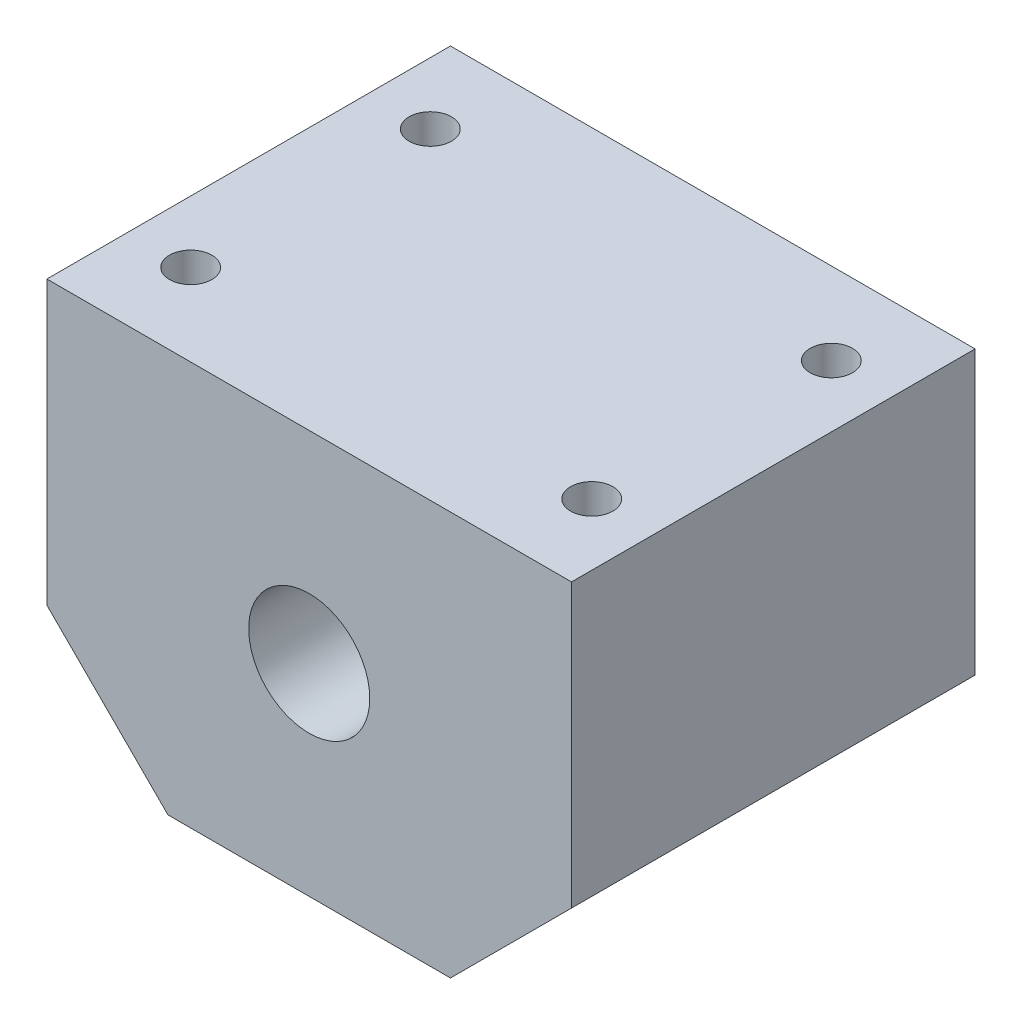
SolidWorks part; units mm, degrees
ref_plane "Front Plane" through (0, 0, 0) normal (0, 0, 1) x (1, 0, 0)
ref_plane "Top Plane" through (0, 0, 0) normal (0, 1, 0) x (1, 0, 0)
ref_plane "Right Plane" through (0, 0, 0) normal (1, 0, 0) x (0, 0, -1)
sketch "Sketch1" plane through (0, 0, 0) normal (0, 0, 1) x (1, 0, 0)
  line L0 (-26, 20) -> (-26, -8)
  line L1 (-26, -8) -> (-14, -20)
  line L2 (-14, -20) -> (14, -20)
  line L3 (-26, 20) -> (26, 20)
  line L4 (0, -55) -> (0, 55) construction
  line L5 (26, -8) -> (14, -20)
  line L6 (26, 20) -> (26, -8)
  line L7 (0, 20) -> (0, -20) construction
  circle A0 centre (0, 0) radius 6
  point P8 (0, 0)
  dimension "D1" = 12
  dimension "D2" = 52
  dimension "D3" = 135
  dimension "D4" = 40
  dimension "D5" = 12
extrude "Boss-Extrude1" add sketch "Sketch1" along normal mid plane 40
sketch "Sketch2" plane through (0, 20, 0) normal (0, 1, 0) x (1, 0, 0)
  line L0 (-19.875, 11.875) -> (19.875, 11.875) construction
  line L1 (-19.875, 11.875) -> (-19.875, -11.875) construction
  circle A0 centre (-19.875, 11.875) radius 2.1
  circle A1 centre (19.875, 11.875) radius 2.1
  circle A2 centre (19.875, -11.875) radius 2.1
  circle A3 centre (-19.875, -11.875) radius 2.1
  point P2 (-19.875, 0)
  point P4 (0, 11.875)
  dimension "D3" = 4.2
  dimension "D4" = 39.75
  dimension "D5" = 23.75
  dimension "D1" = 2
  dimension "D2" = 2
extrude "Cut-Extrude1" cut sketch "Sketch2" against normal blind 16
